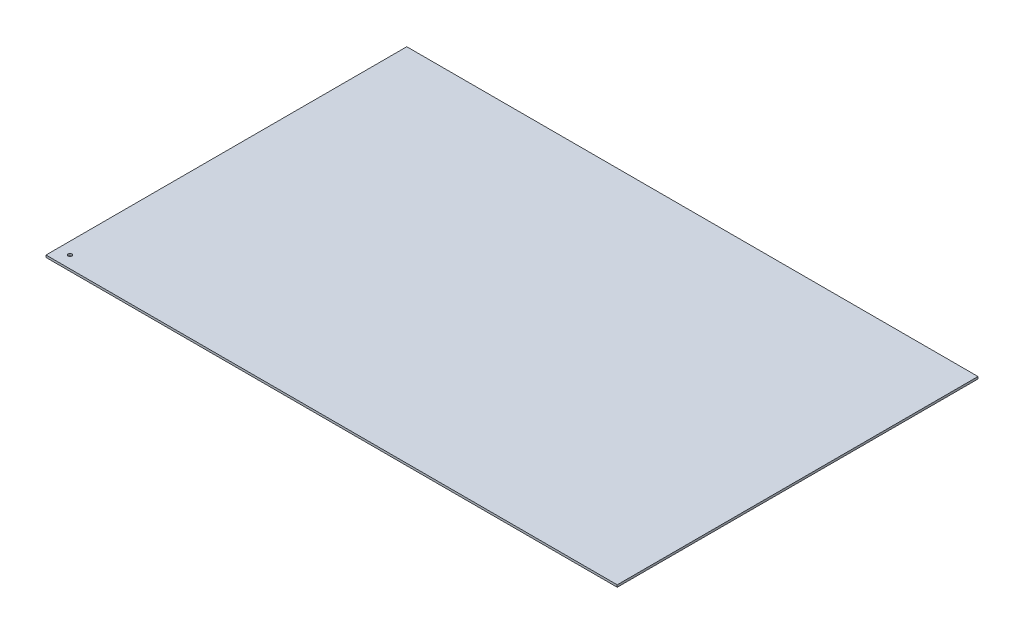
SolidWorks part; units mm, degrees
ref_plane "Front Plane" through (0, 0, 0) normal (0, 0, 1) x (1, 0, 0)
ref_plane "Top Plane" through (0, 0, 0) normal (0, 1, 0) x (1, 0, 0)
ref_plane "Right Plane" through (0, 0, 0) normal (1, 0, 0) x (0, 0, -1)
sketch "Sketch1" plane through (0, 0, 0) normal (0, 1, 0) x (1, 0, 0)
  line L0 (0, 0) -> (0, 381)
  line L1 (0, 381) -> (603.25, 381)
  line L2 (603.25, 381) -> (603.25, 0)
  line L3 (603.25, 0) -> (0, 0)
  dimension "D1" = 381
  dimension "D2" = 603.25
extrude "Boss-Extrude1" add sketch "Sketch1" along normal blind 2.286 contours L1 L2 L3 L0
sketch "Sketch2" plane through (0, 2.286, 0) normal (0, 1, 0) x (1, 0, 0)
  line L0 (0, 0) -> (0, 381) construction
  line L1 (603.25, 0) -> (0, 0) construction
  circle A0 centre (12.7, 12.7) radius 2.032
  dimension "D1" = 4.064
  dimension "D2" = 12.7
  dimension "D3" = 12.7
extrude "Cut-Extrude1" cut sketch "Sketch2" against normal blind 22.86 contours A0
